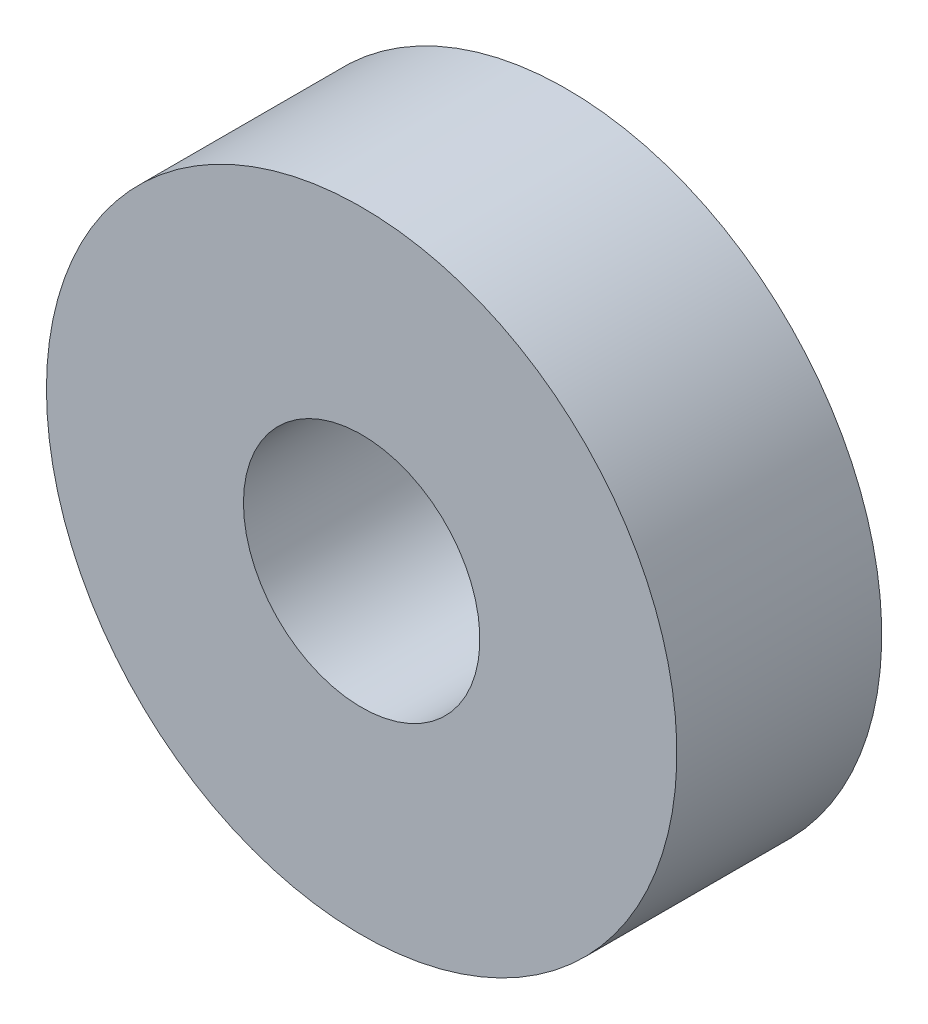
SolidWorks part; units mm, degrees
material "Alloy Steel"
ref_plane "Front Plane" through (0, 0, 0) normal (0, 0, 1) x (1, 0, 0)
ref_plane "Top Plane" through (0, 0, 0) normal (0, 1, 0) x (1, 0, 0)
ref_plane "Right Plane" through (0, 0, 0) normal (1, 0, 0) x (0, 0, -1)
sketch "Sketch1" plane through (0, 0, 0) normal (0, 0, 1) x (1, 0, 0)
  circle A0 centre (0, 0) radius 20
  circle A1 centre (0, 0) radius 7.5
  dimension "D1" = 40
  dimension "D2" = 15
extrude "Boss-Extrude1" add sketch "Sketch1" along normal blind 13
